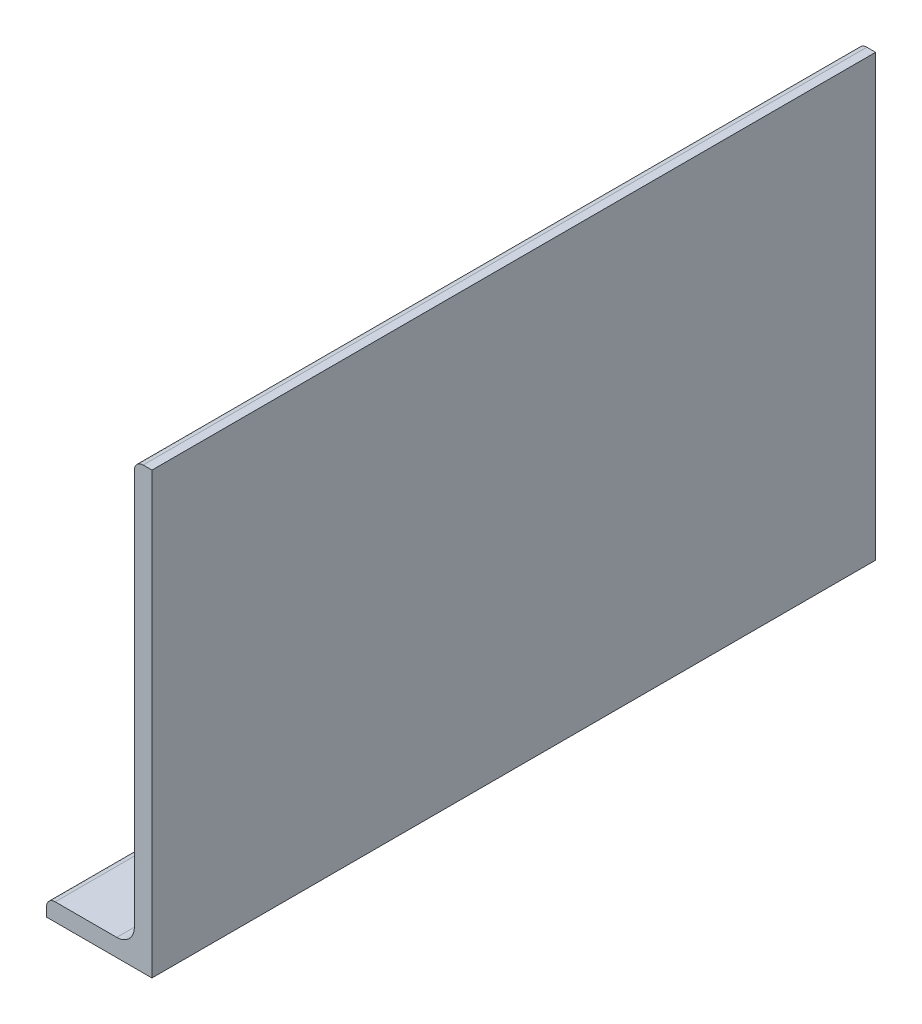
SolidWorks part; units mm, degrees
ref_plane "Front Plane" through (0, 0, 0) normal (0, 0, 1) x (1, 0, 0)
ref_plane "Top Plane" through (0, 0, 0) normal (0, 1, 0) x (1, 0, 0)
ref_plane "Right Plane" through (0, 0, 0) normal (1, 0, 0) x (0, 0, -1)
sketch "Sketch1" plane through (0, 0, 0) normal (0, 0, 1) x (1, 0, 0)
  line L0 (468.753, -2.5122) -> (468.753, -52.5122)
  line L1 (468.753, -52.5122) -> (456.753, -52.5122)
  line L2 (456.753, -52.5122) -> (456.753, -50.5122)
  line L3 (456.753, -50.5122) -> (466.753, -50.5122)
  line L4 (466.753, -50.5122) -> (466.753, -2.5122)
  line L5 (466.753, -2.5122) -> (468.753, -2.5122)
  dimension "D1" = 2
  dimension "D2" = 2
  dimension "D3" = 50
  dimension "D4" = 12
extrude "Boss-Extrude1" add sketch "Sketch1" along normal blind 82.26
fillet "Fillet1" radius 1 2 edges at (456.753, -50.5122, 41.13) (466.753, -2.5122, 41.13)
fillet "Fillet2" radius 2 1 edges at (466.753, -50.5122, 41.13)
sketch "Sketch2" plane through (0, -50.5122, 0) normal (0, 1, 0) x (1, 0, 0)
  line L0 (468.753, -82.26) -> (468.753, 0) construction
  line L1 (464.753, 0) -> (457.753, 0) construction
  line L2 (464.753, -82.26) -> (457.753, -82.26) construction
  circle A0 centre (461.253, -67.26) radius 1.6
  circle A1 centre (461.253, -15) radius 1.6
  dimension "D1" = 3.2
  dimension "D2" = 3.2
  dimension "D3" = 7.5
  dimension "D4" = 7.5
  dimension "D5" = 15
  dimension "D6" = 15
extrude "Cut-Extrude1" cut sketch "Sketch2" against normal through all
